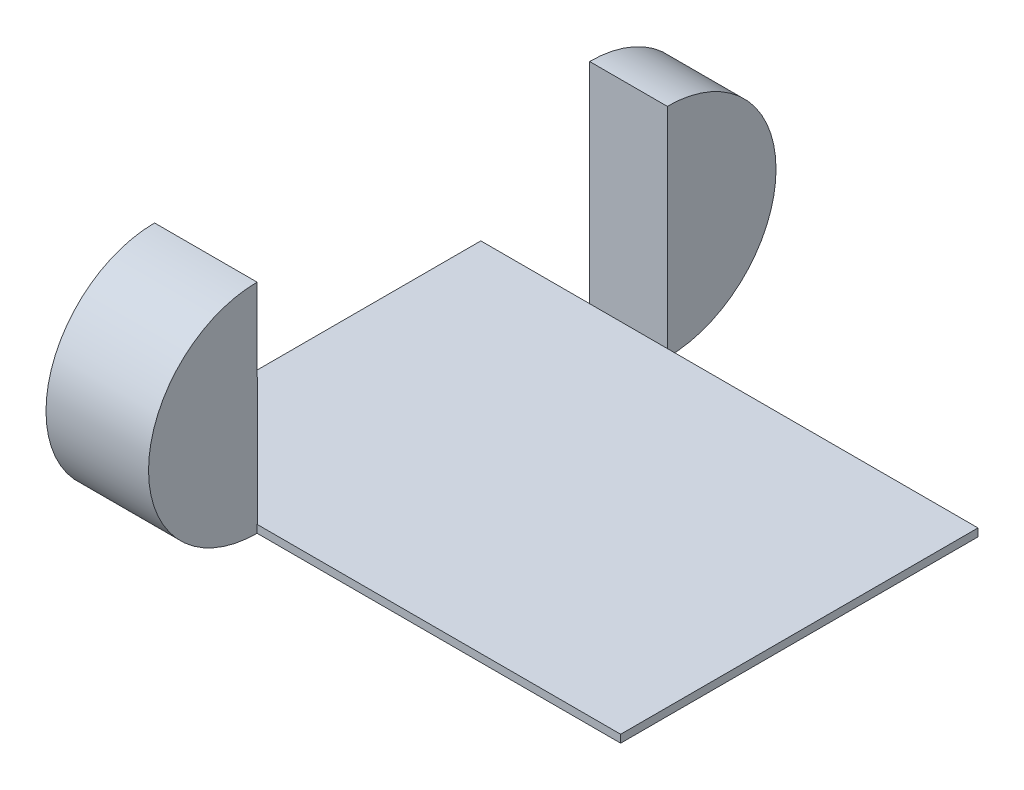
SolidWorks part; units mm, degrees
ref_plane "前视基准面" through (0, 0, 0) normal (0, 0, 1) x (1, 0, 0)
ref_plane "上视基准面" through (0, 0, 0) normal (0, 1, 0) x (1, 0, 0)
ref_plane "右视基准面" through (0, 0, 0) normal (1, 0, 0) x (0, 0, -1)
sketch "草图1" plane through (0, 0, 0) normal (0, 1, 0) x (1, 0, 0)
  line L1 (-16, 11.5) -> (16, 11.5)
  line L2 (-16, 11.5) -> (-16, -11.5)
  line L3 (-16, -11.5) -> (16, -11.5)
  line L4 (16, 11.5) -> (16, -11.5)
  line L5 (-16, 11.5) -> (16, -11.5) construction
  line L6 (-16, -11.5) -> (16, 11.5) construction
  point P0 (0, 0)
extrude "凸台-拉伸1" add sketch "草图1" along normal blind 0.5
sketch "草图4" plane through (0, 0, -11.5) normal (0, 0, -1) x (-1, 0, 0)
  line L0 (16, 0) -> (9, 0) construction
  line L1 (-16, 0) -> (16, 0) construction
  line L2 (9, 0) -> (9, 14) construction
ref_plane "基准面2" through (-9, 0, 0) normal (-1, 0, 0) x (0, 0, 1)
sketch "草图5" plane through (-9, 0, 0) normal (-1, 0, 0) x (0, 0, 1)
  line L0 (-11.5, 0) -> (-11.5, 14)
  arc A0 (-11.5, 14) -> (-11.5, 0) centre (-11.5, 7) ccw
extrude "凸台-拉伸3" add sketch "草图5" against normal blind 5
sketch "草图6" plane through (0, 0, 11.5) normal (0, 0, 1) x (1, 0, 0)
  line L0 (-16, 0.5) -> (-14, 0.5) construction
  line L1 (-16, 0.5) -> (16, 0.5) construction
  line L2 (-14, 0.5) -> (-14, 14.5) construction
ref_plane "基准面3" through (-14, 0, 0) normal (-1, 0, 0) x (0, 0, 1)
sketch "草图7" plane through (-14, 0, 0) normal (-1, 0, 0) x (0, 0, 1)
  line L0 (11.4733, 0) -> (11.5, 14)
  line L2 (11.5, 0.5) -> (11.5, 14.5) construction
  arc A0 (11.4733, 0) -> (11.5, 14) centre (11.4867, 7) ccw
extrude "凸台-拉伸4" add sketch "草图7" against normal blind 6.6
